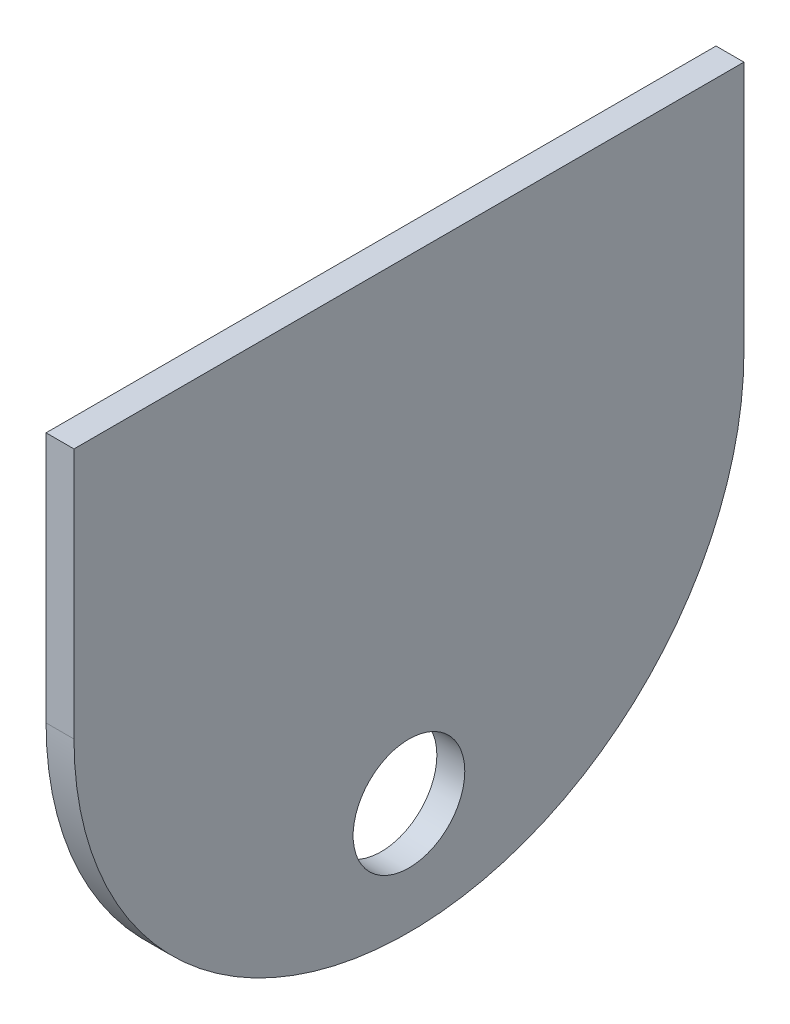
SolidWorks part; units mm, degrees
material "6061 Alloy"
ref_plane "Front Plane" through (0, 0, 0) normal (0, 0, 1) x (1, 0, 0)
ref_plane "Top Plane" through (0, 0, 0) normal (0, 1, 0) x (1, 0, 0)
ref_plane "Right Plane" through (0, 0, 0) normal (1, 0, 0) x (0, 0, -1)
sketch "Sketch1" plane through (0, 0, 0) normal (1, 0, 0) x (0, 0, -1)
  line L3 (-38.1, 0) -> (-38.1, 28.575)
  line L4 (-38.1, 28.575) -> (38.1, 28.575)
  line L5 (38.1, 28.575) -> (38.1, 0)
  arc A1 (-38.1, 0) -> (38.1, 0) centre (0, 0) ccw
  dimension "D2" = 28.575
  dimension "D1" = 38.1
extrude "Boss-Extrude1" add sketch "Sketch1" along normal blind 3.175
sketch "Sketch2" plane through (3.175, 0, 0) normal (1, 0, 0) x (0, 0, -1)
  line L0 (0, -38.1) -> (0, -25.4) construction
  line L1 (0, 0) -> (0, -25.4) construction
  arc A0 (-38.1, 0) -> (38.1, 0) centre (0, 0) ccw construction
  circle A1 centre (0, -25.4) radius 6.35
  dimension "D1" = 12.7
  dimension "D2" = 25.4
extrude "Cut-Extrude1" cut sketch "Sketch2" against normal through all
